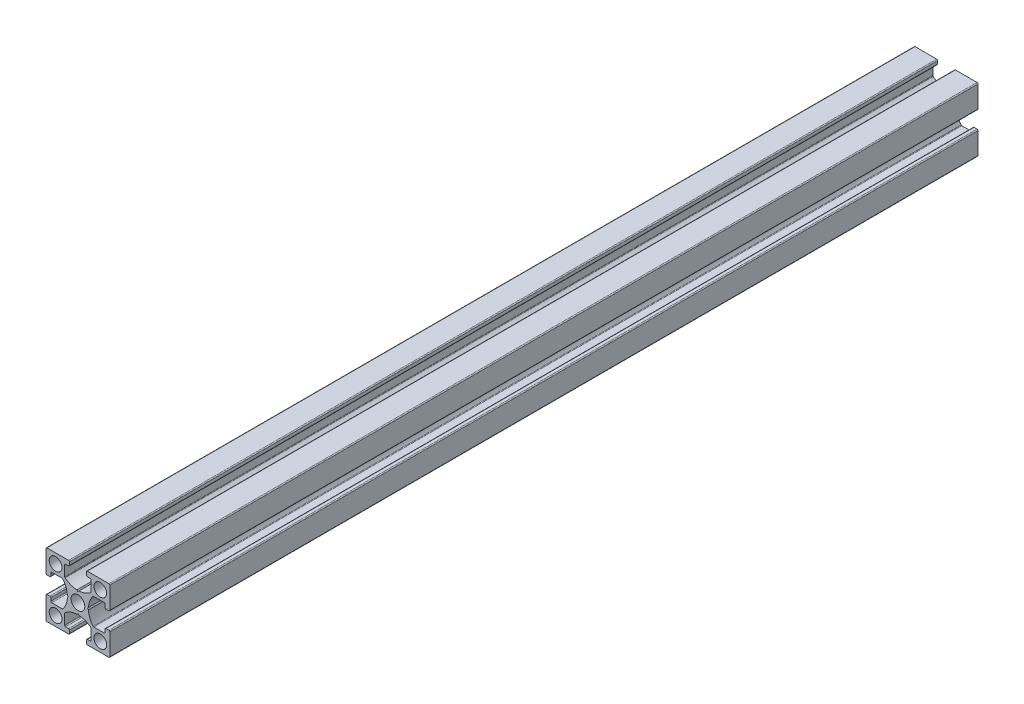
SolidWorks part; units mm, degrees
ref_plane "정면" through (0, 0, 0) normal (0, 0, 1) x (1, 0, 0)
ref_plane "윗면" through (0, 0, 0) normal (0, 1, 0) x (1, 0, 0)
ref_plane "우측면" through (0, 0, 0) normal (1, 0, 0) x (0, 0, -1)
sketch "Model" plane through (0, 0, 0) normal (0, 0, 1) x (1, 0, 0)
  line L0 (2292.4151, 1187.1915) -> (2314.8128, 1187.1915) construction
  line L1 (2307.7639, 1192.1343) -> (2307.7639, 1195.3915)
  line L2 (2307.4639, 1195.6915) -> (2306.5639, 1195.6915)
  line L3 (2306.2639, 1195.9915) -> (2306.2639, 1196.8915)
  line L4 (2306.5639, 1197.1915) -> (2313.3139, 1197.1915)
  line L5 (2313.6139, 1196.8915) -> (2313.6139, 1190.1415)
  line L6 (2313.3139, 1189.8415) -> (2312.4139, 1189.8415)
  line L7 (2312.1139, 1190.1415) -> (2312.1139, 1191.0415)
  line L8 (2311.8139, 1191.3415) -> (2308.5567, 1191.3415)
  line L9 (2306.9212, 1187.4988) -> (2306.6139, 1187.1915)
  line L10 (2306.6139, 1187.1915) -> (2306.9212, 1186.8843)
  line L11 (2308.5567, 1183.0415) -> (2311.8139, 1183.0415)
  line L12 (2312.1139, 1183.3415) -> (2312.1139, 1184.2415)
  line L13 (2312.4139, 1184.5415) -> (2313.3139, 1184.5415)
  line L14 (2313.6139, 1184.2415) -> (2313.6139, 1177.4915)
  line L15 (2313.3139, 1177.1915) -> (2306.5639, 1177.1915)
  line L16 (2306.2639, 1177.4915) -> (2306.2639, 1178.3915)
  line L17 (2306.5639, 1178.6915) -> (2307.4639, 1178.6915)
  line L18 (2307.7639, 1178.9915) -> (2307.7639, 1182.2488)
  line L19 (2303.9212, 1183.8843) -> (2303.6139, 1184.1915)
  line L20 (2303.6139, 1184.1915) -> (2303.3066, 1183.8843)
  line L21 (2299.4639, 1182.2488) -> (2299.4639, 1178.9915)
  line L22 (2299.7639, 1178.6915) -> (2300.6639, 1178.6915)
  line L23 (2300.9639, 1178.3915) -> (2300.9639, 1177.4915)
  line L24 (2300.6639, 1177.1915) -> (2293.9139, 1177.1915)
  line L25 (2293.6139, 1177.4915) -> (2293.6139, 1184.2415)
  line L26 (2293.9139, 1184.5415) -> (2294.8139, 1184.5415)
  line L27 (2295.1139, 1184.2415) -> (2295.1139, 1183.3415)
  line L28 (2295.4139, 1183.0415) -> (2298.6712, 1183.0415)
  line L29 (2300.3066, 1186.8843) -> (2300.6139, 1187.1915)
  line L30 (2300.6139, 1187.1915) -> (2300.3066, 1187.4988)
  line L31 (2298.6712, 1191.3415) -> (2295.4139, 1191.3415)
  line L32 (2295.1139, 1191.0415) -> (2295.1139, 1190.1415)
  line L33 (2294.8139, 1189.8415) -> (2293.9139, 1189.8415)
  line L34 (2293.6139, 1190.1415) -> (2293.6139, 1196.8915)
  line L35 (2293.9139, 1197.1915) -> (2300.6639, 1197.1915)
  line L36 (2300.9639, 1196.8915) -> (2300.9639, 1195.9915)
  line L37 (2300.6639, 1195.6915) -> (2299.7639, 1195.6915)
  line L38 (2299.4639, 1195.3915) -> (2299.4639, 1192.1343)
  line L39 (2303.3066, 1190.4988) -> (2303.6139, 1190.1915)
  line L40 (2303.6139, 1190.1915) -> (2303.9212, 1190.4988)
  line L41 (2294.1139, 1194.1915) -> (2299.1139, 1194.1915) construction
  line L42 (2296.6139, 1196.6915) -> (2296.6139, 1191.6915) construction
  line L43 (2294.1139, 1180.1915) -> (2299.1139, 1180.1915) construction
  line L44 (2296.6139, 1177.6915) -> (2296.6139, 1182.6915) construction
  line L45 (2303.6139, 1198.3904) -> (2303.6139, 1175.9927) construction
  line L46 (2313.1139, 1194.1915) -> (2308.1139, 1194.1915) construction
  line L47 (2310.6139, 1196.6915) -> (2310.6139, 1191.6915) construction
  line L48 (2310.6139, 1177.6915) -> (2310.6139, 1182.6915) construction
  line L49 (2313.1139, 1180.1915) -> (2308.1139, 1180.1915) construction
  circle A0 centre (2303.6139, 1187.1915) radius 2.15
  circle A1 centre (2296.6139, 1194.1915) radius 2
  circle A2 centre (2296.6139, 1180.1915) radius 2
  circle A3 centre (2310.6139, 1194.1915) radius 2
  circle A4 centre (2310.6139, 1180.1915) radius 2
  arc A5 (2307.7639, 1195.3915) -> (2307.4639, 1195.6915) centre (2307.4639, 1195.3915) ccw
  arc A6 (2306.2639, 1195.9915) -> (2306.5639, 1195.6915) centre (2306.5639, 1195.9915) ccw
  arc A7 (2306.5639, 1197.1915) -> (2306.2639, 1196.8915) centre (2306.5639, 1196.8915) ccw
  arc A8 (2313.6139, 1196.8915) -> (2313.3139, 1197.1915) centre (2313.3139, 1196.8915) ccw
  arc A9 (2313.3139, 1189.8415) -> (2313.6139, 1190.1415) centre (2313.3139, 1190.1415) ccw
  arc A10 (2312.1139, 1190.1415) -> (2312.4139, 1189.8415) centre (2312.4139, 1190.1415) ccw
  arc A11 (2312.1139, 1191.0415) -> (2311.8139, 1191.3415) centre (2311.8139, 1191.0415) ccw
  arc A12 (2308.5567, 1191.3415) -> (2308.3217, 1191.2281) centre (2308.5567, 1191.0415) ccw
  arc A13 (2308.3217, 1191.2281) -> (2306.9212, 1187.4988) centre (2313.4048, 1187.1915) ccw
  arc A14 (2306.9212, 1186.8843) -> (2308.3217, 1183.155) centre (2313.4048, 1187.1915) ccw
  arc A15 (2308.3217, 1183.155) -> (2308.5567, 1183.0415) centre (2308.5567, 1183.3415) ccw
  arc A16 (2311.8139, 1183.0415) -> (2312.1139, 1183.3415) centre (2311.8139, 1183.3415) ccw
  arc A17 (2312.4139, 1184.5415) -> (2312.1139, 1184.2415) centre (2312.4139, 1184.2415) ccw
  arc A18 (2313.6139, 1184.2415) -> (2313.3139, 1184.5415) centre (2313.3139, 1184.2415) ccw
  arc A19 (2313.3139, 1177.1915) -> (2313.6139, 1177.4915) centre (2313.3139, 1177.4915) ccw
  arc A20 (2306.2639, 1177.4915) -> (2306.5639, 1177.1915) centre (2306.5639, 1177.4915) ccw
  arc A21 (2306.5639, 1178.6915) -> (2306.2639, 1178.3915) centre (2306.5639, 1178.3915) ccw
  arc A22 (2307.4639, 1178.6915) -> (2307.7639, 1178.9915) centre (2307.4639, 1178.9915) ccw
  arc A23 (2307.7639, 1182.2488) -> (2307.6505, 1182.4837) centre (2307.4639, 1182.2488) ccw
  arc A24 (2307.6505, 1182.4837) -> (2303.9212, 1183.8843) centre (2303.6139, 1177.4007) ccw
  arc A25 (2303.3066, 1183.8843) -> (2299.5774, 1182.4837) centre (2303.6139, 1177.4007) ccw
  arc A26 (2299.5774, 1182.4837) -> (2299.4639, 1182.2488) centre (2299.7639, 1182.2488) ccw
  arc A27 (2299.4639, 1178.9915) -> (2299.7639, 1178.6915) centre (2299.7639, 1178.9915) ccw
  arc A28 (2300.9639, 1178.3915) -> (2300.6639, 1178.6915) centre (2300.6639, 1178.3915) ccw
  arc A29 (2300.6639, 1177.1915) -> (2300.9639, 1177.4915) centre (2300.6639, 1177.4915) ccw
  arc A30 (2293.6139, 1177.4915) -> (2293.9139, 1177.1915) centre (2293.9139, 1177.4915) ccw
  arc A31 (2293.9139, 1184.5415) -> (2293.6139, 1184.2415) centre (2293.9139, 1184.2415) ccw
  arc A32 (2295.1139, 1184.2415) -> (2294.8139, 1184.5415) centre (2294.8139, 1184.2415) ccw
  arc A33 (2295.1139, 1183.3415) -> (2295.4139, 1183.0415) centre (2295.4139, 1183.3415) ccw
  arc A34 (2298.6712, 1183.0415) -> (2298.9061, 1183.155) centre (2298.6712, 1183.3415) ccw
  arc A35 (2298.9061, 1183.155) -> (2300.3066, 1186.8843) centre (2293.8231, 1187.1915) ccw
  arc A36 (2300.3066, 1187.4988) -> (2298.9061, 1191.2281) centre (2293.8231, 1187.1915) ccw
  arc A37 (2298.9061, 1191.2281) -> (2298.6712, 1191.3415) centre (2298.6712, 1191.0415) ccw
  arc A38 (2295.4139, 1191.3415) -> (2295.1139, 1191.0415) centre (2295.4139, 1191.0415) ccw
  arc A39 (2294.8139, 1189.8415) -> (2295.1139, 1190.1415) centre (2294.8139, 1190.1415) ccw
  arc A40 (2293.6139, 1190.1415) -> (2293.9139, 1189.8415) centre (2293.9139, 1190.1415) ccw
  arc A41 (2293.9139, 1197.1915) -> (2293.6139, 1196.8915) centre (2293.9139, 1196.8915) ccw
  arc A42 (2300.9639, 1196.8915) -> (2300.6639, 1197.1915) centre (2300.6639, 1196.8915) ccw
  arc A43 (2300.6639, 1195.6915) -> (2300.9639, 1195.9915) centre (2300.6639, 1195.9915) ccw
  arc A44 (2299.7639, 1195.6915) -> (2299.4639, 1195.3915) centre (2299.7639, 1195.3915) ccw
  arc A45 (2299.4639, 1192.1343) -> (2299.5774, 1191.8994) centre (2299.7639, 1192.1343) ccw
  arc A46 (2299.5774, 1191.8994) -> (2303.3066, 1190.4988) centre (2303.6139, 1196.9824) ccw
  arc A47 (2303.9212, 1190.4988) -> (2307.6505, 1191.8994) centre (2303.6139, 1196.9824) ccw
  arc A48 (2307.6505, 1191.8994) -> (2307.7639, 1192.1343) centre (2307.4639, 1192.1343) ccw
extrude "보스-돌출1" add sketch "Model" along normal blind 272
